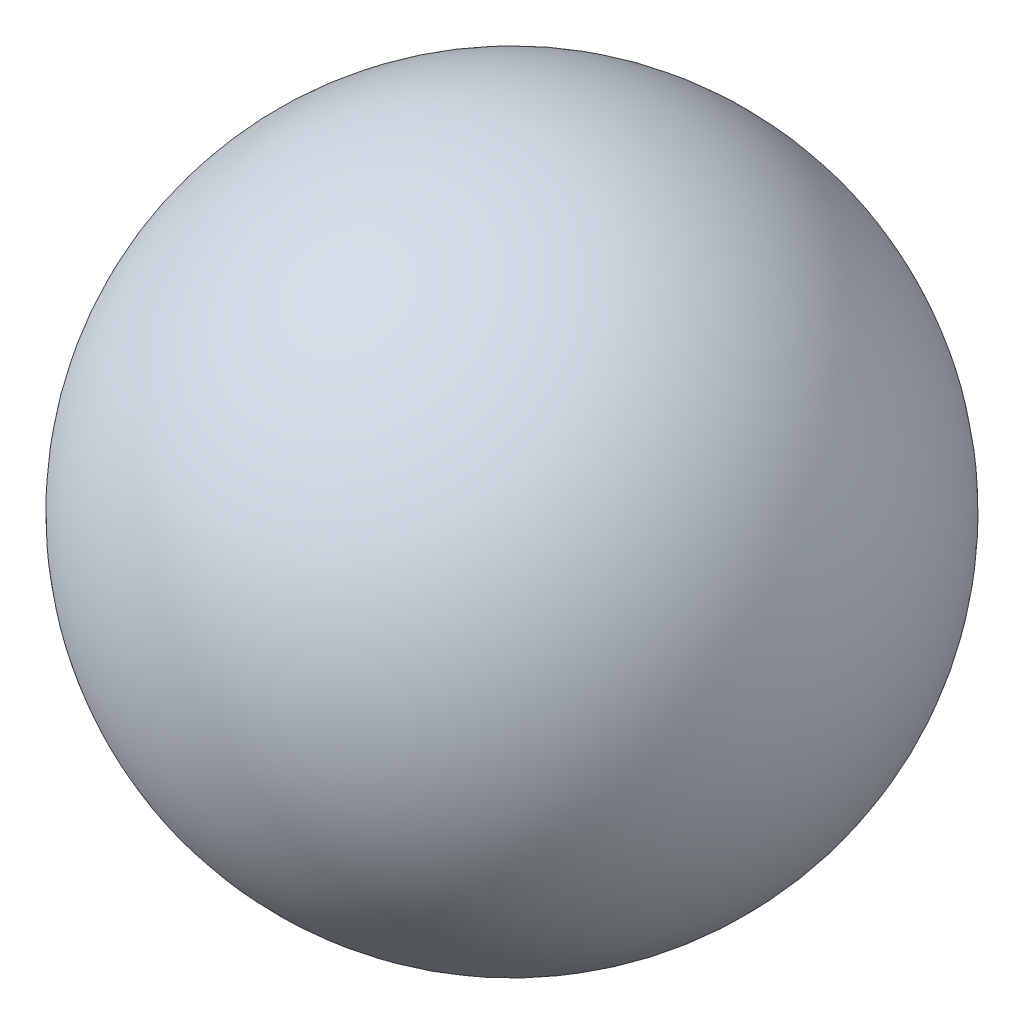
SolidWorks part; units mm, degrees
material "ABS"
ref_plane "Front Plane" through (0, 0, 0) normal (0, 0, 1) x (1, 0, 0)
ref_plane "Top Plane" through (0, 0, 0) normal (0, 1, 0) x (1, 0, 0)
ref_plane "Right Plane" through (0, 0, 0) normal (1, 0, 0) x (0, 0, -1)
sketch "Sketch1" plane through (0, 0, 0) normal (0, 1, 0) x (1, 0, 0)
  line L0 (0, 8) -> (0, -8)
  arc A0 (0, 8) -> (0, -8) centre (0, 0) ccw
  dimension "D1" = 16
revolve "Revolve1" add sketch "Sketch1" angle 360 about L0
sketch "Sketch3" plane through (0, 0, 0) normal (0, 1, 0) x (1, 0, 0)
  circle A0 centre (0, 0) radius 8
